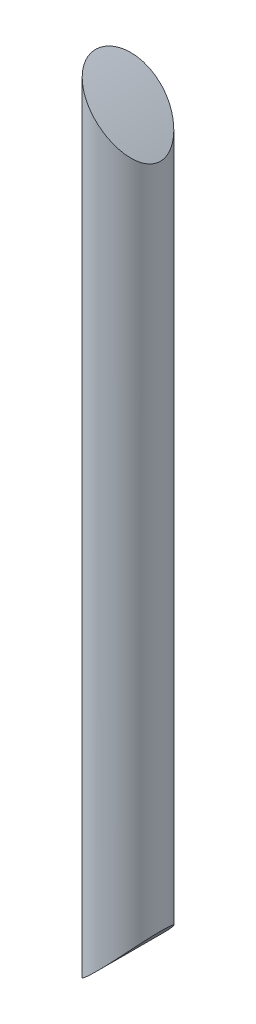
SolidWorks part; units mm, degrees
material "Polylactide (PLA)"
ref_plane "Front Plane" through (0, 0, 0) normal (0, 0, 1) x (1, 0, 0)
ref_plane "Top Plane" through (0, 0, 0) normal (0, 1, 0) x (1, 0, 0)
ref_plane "Right Plane" through (0, 0, 0) normal (1, 0, 0) x (0, 0, -1)
sketch "Sketch1" plane through (0, 0, 0) normal (0, 1, 0) x (1, 0, 0)
  circle A0 centre (0, 0) radius 2
  dimension "D1" = 4
extrude "Boss-Extrude1" add sketch "Sketch1" along normal blind 70
sketch "Sketch3" plane through (0, 0, 0) normal (0, 0, 1) x (1, 0, 0)
  line L0 (0, 70) -> (0, 0) construction
  line L1 (2, 70) -> (-2, 70) construction
  line L2 (0, 35) -> (-22.5, 35) construction
  circle A0 centre (-22.5, 35) radius 32
  circle A1 centre (-22.5, 35) radius 62.2056
  point P5 (0, 35)
  dimension "D1" = 64
  dimension "D3" = 124.4112
  dimension "D2" = 22.5
extrude "Cut-Extrude1" cut sketch "Sketch3" against normal through all both and the other way through all
